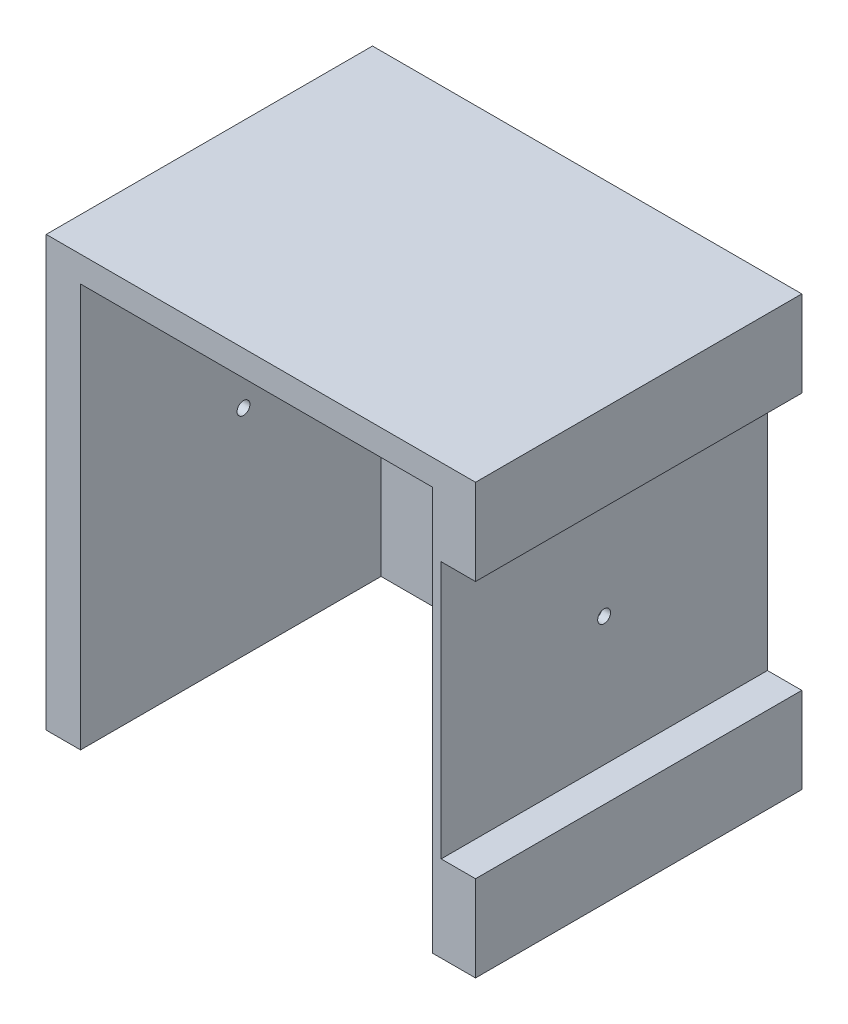
SolidWorks part; units mm, degrees
ref_plane "Front Plane" through (0, 0, 0) normal (0, 0, 1) x (1, 0, 0)
ref_plane "Top Plane" through (0, 0, 0) normal (0, 1, 0) x (1, 0, 0)
ref_plane "Right Plane" through (0, 0, 0) normal (1, 0, 0) x (0, 0, -1)
sketch "Sketch8" plane through (0, 0, 0) normal (0, 0, 1) x (1, 0, 0)
  line L1 (-25, 25) -> (25, 25)
  line L2 (-25, 25) -> (-25, -25)
  line L3 (-25, -25) -> (25, -25)
  line L4 (25, 25) -> (25, -25)
  line L5 (-25, 25) -> (25, -25) construction
  line L6 (-25, -25) -> (25, 25) construction
  point P0 (0, 0)
  dimension "D1" = 50
  dimension "D2" = 50
extrude "Boss-Extrude7" add sketch "Sketch8" along normal blind 3
sketch "Sketch9" plane through (25, 0, 0) normal (1, 0, 0) x (0, 0, -1)
  line L1 (0, 25) -> (-38, 25)
  line L2 (0, 25) -> (0, -25)
  line L3 (0, -25) -> (-38, -25)
  line L4 (-38, 25) -> (-38, -25)
  dimension "D1" = 50
  dimension "D2" = 38
extrude "Boss-Extrude8" add sketch "Sketch9" against normal blind 5
sketch "Sketch10" plane through (-25, 0, 0) normal (-1, 0, 0) x (0, 0, 1)
  line L1 (0, 25) -> (38, 25)
  line L2 (0, 25) -> (0, -25)
  line L3 (0, -25) -> (38, -25)
  line L4 (38, 25) -> (38, -25)
extrude "Boss-Extrude9" add sketch "Sketch10" against normal blind 4
sketch "Sketch11" plane through (0, 25, 0) normal (0, 1, 0) x (1, 0, 0)
  line L1 (-25, 0) -> (25, 0)
  line L2 (-25, 0) -> (-25, -38)
  line L3 (-25, -38) -> (25, -38)
  line L4 (25, 0) -> (25, -38)
extrude "Boss-Extrude10" add sketch "Sketch11" against normal blind 3
sketch "Sketch13" plane through (25, 0, 0) normal (1, 0, 0) x (0, 0, -1)
  line L0 (-38, -25) -> (-19, -25)
  line L1 (-38, -25) -> (0, -25) construction
  line L3 (0, -25) -> (0, 25) construction
  line L4 (-38, 14.9878) -> (0, 14.9878)
  line L5 (-38, 14.9878) -> (-38, -14.9878)
  line L6 (-38, -14.9878) -> (0, -14.9878)
  line L7 (0, 14.9878) -> (0, -14.9878)
  line L8 (-38, 14.9878) -> (0, -14.9878) construction
  line L9 (-38, -14.9878) -> (0, 14.9878) construction
  line M1 (-38, 25) -> (-38, -25)
  line M3 (0, -25) -> (0, 25)
extrude "Cut-Extrude1" cut sketch "Sketch13" against normal blind 4 contours L6 L4 M1 M3
sketch "Sketch14" plane through (-25, 0, 0) normal (-1, 0, 0) x (0, 0, 1)
  circle A0 centre (19.0213, 0) radius 0.75
extrude "Cut-Extrude3" cut sketch "Sketch14" against normal blind 68
